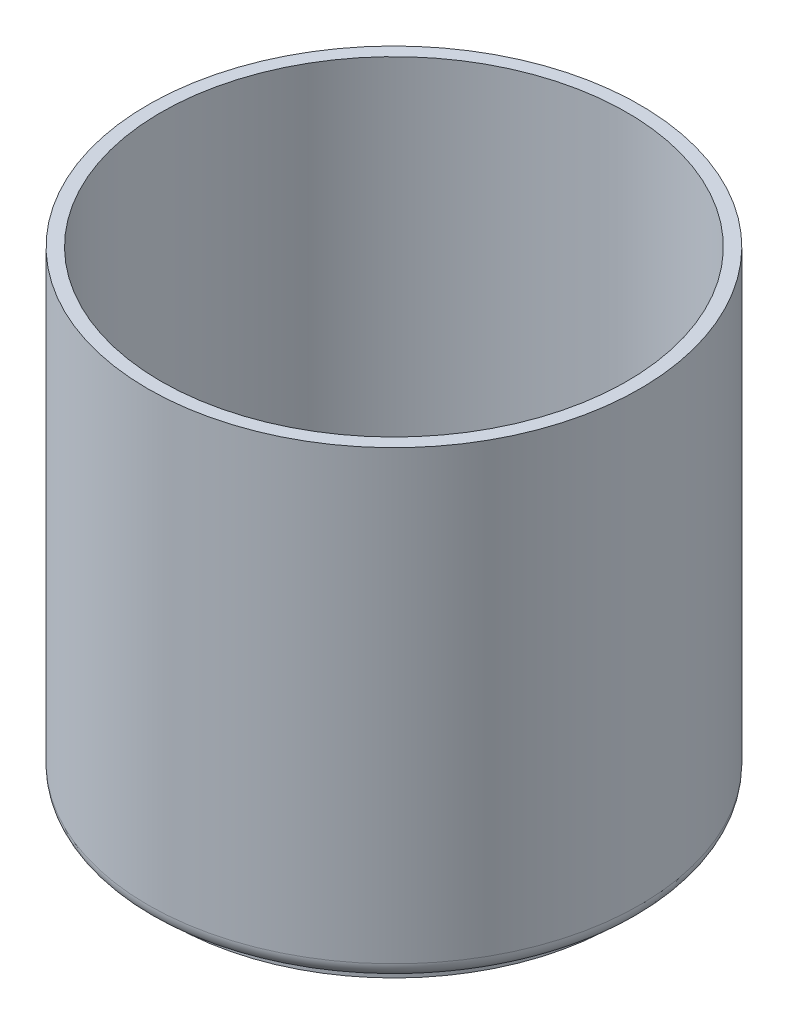
SolidWorks part; units mm, degrees
ref_plane "Front Plane" through (0, 0, 0) normal (0, 0, 1) x (1, 0, 0)
ref_plane "Top Plane" through (0, 0, 0) normal (0, 1, 0) x (1, 0, 0)
ref_plane "Right Plane" through (0, 0, 0) normal (1, 0, 0) x (0, 0, -1)
sketch "Sketch1" plane through (0, 0, 0) normal (0, 1, 0) x (1, 0, 0)
  circle A0 centre (0, 0) radius 86.36
  circle A1 centre (0, 0) radius 80.518
  dimension "D1" = 172.72
  dimension "D2" = 5.842
extrude "Boss-Extrude1" add sketch "Sketch1" along normal blind 5.08
sketch "Sketch2" plane through (0, 5.08, 0) normal (0, 1, 0) x (1, 0, 0)
  circle A0 centre (0, 0) radius 95.758
  circle A1 centre (0, 0) radius 80.518 construction
  dimension "D1" = 15.24
extrude "Boss-Extrude2" add sketch "Sketch2" along normal blind 5.08
sketch "Sketch3" plane through (0, 10.16, 0) normal (0, 1, 0) x (1, 0, 0)
  circle A0 centre (0, 0) radius 90.678
  circle A1 centre (0, 0) radius 95.758 construction
  circle A2 centre (0, 0) radius 95.758
  dimension "D1" = 5.08
extrude "Boss-Extrude3" add sketch "Sketch3" along normal blind 175.26
fillet "Fillet1" radius 6.35 2 edges at (0, 10.16, 90.678) (0, 5.08, 95.758)
